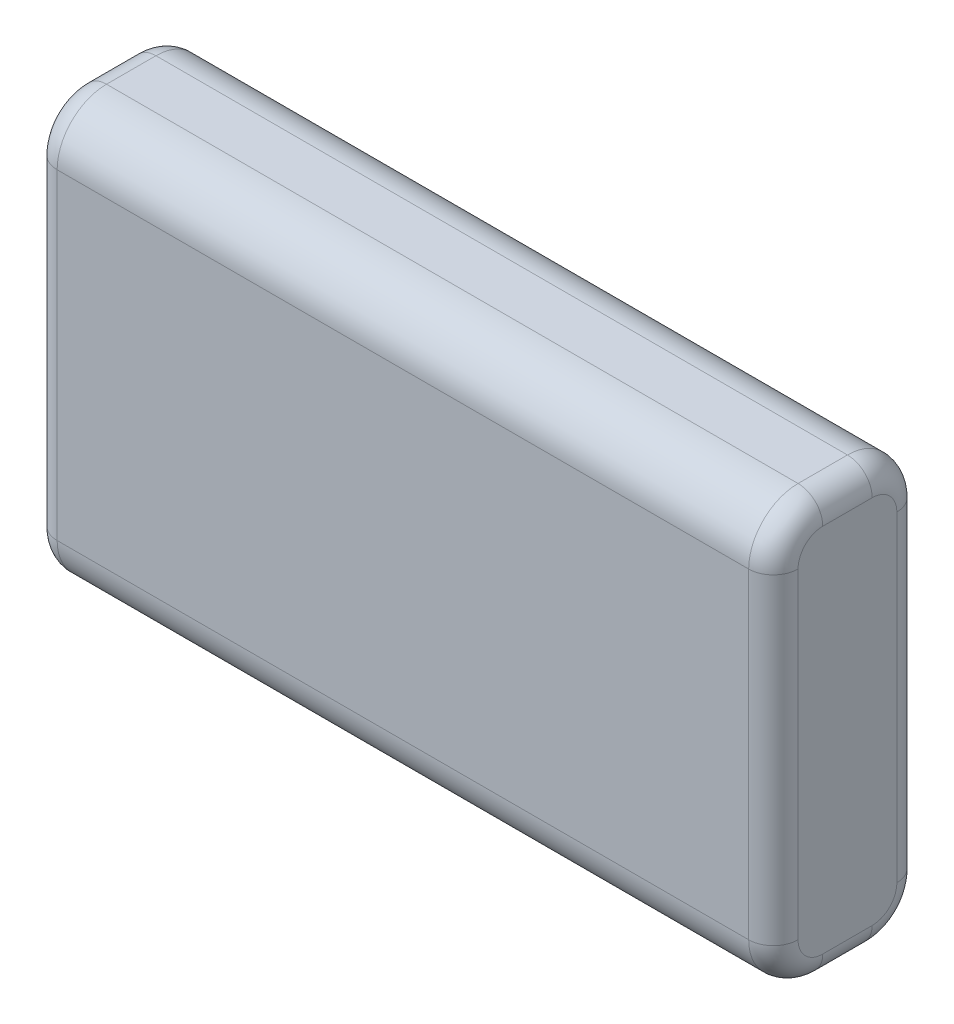
SolidWorks part; units mm, degrees
ref_plane "Front Plane" through (0, 0, 0) normal (0, 0, 1) x (1, 0, 0)
ref_plane "Top Plane" through (0, 0, 0) normal (0, 1, 0) x (1, 0, 0)
ref_plane "Right Plane" through (0, 0, 0) normal (1, 0, 0) x (0, 0, -1)
sketch "Sketch1" plane through (0, 0, 0) normal (0, 0, 1) x (1, 0, 0)
  line L1 (0, 0) -> (30, 0)
  line L2 (0, 0) -> (0, 17)
  line L3 (0, 17) -> (30, 17)
  line L4 (30, 0) -> (30, 17)
  dimension "D1" = 30
  dimension "D2" = 17
extrude "Boss-Extrude1" add sketch "Sketch1" along normal blind 6
fillet "Fillet1" radius 2 4 edges at (15, 0, 0) (15, 0, 6) (15, 17, 6) (15, 17, 0)
fillet "Fillet2" radius 1 16 edges at (0, 16.4142, 5.4142) (0, 17, 3) (0, 16.4142, 0.5858) (0, 8.5, 0) (0, 0.5858, 0.5858) (0, 0, 3) (0, 0.5858, 5.4142) (30, 0.5858, 5.4142) (30, 0, 3) (30, 0.5858, 0.5858) (30, 8.5, 0) (30, 16.4142, 0.5858) (30, 17, 3) (30, 16.4142, 5.4142) (0, 8.5, 6) (30, 8.5, 6)
